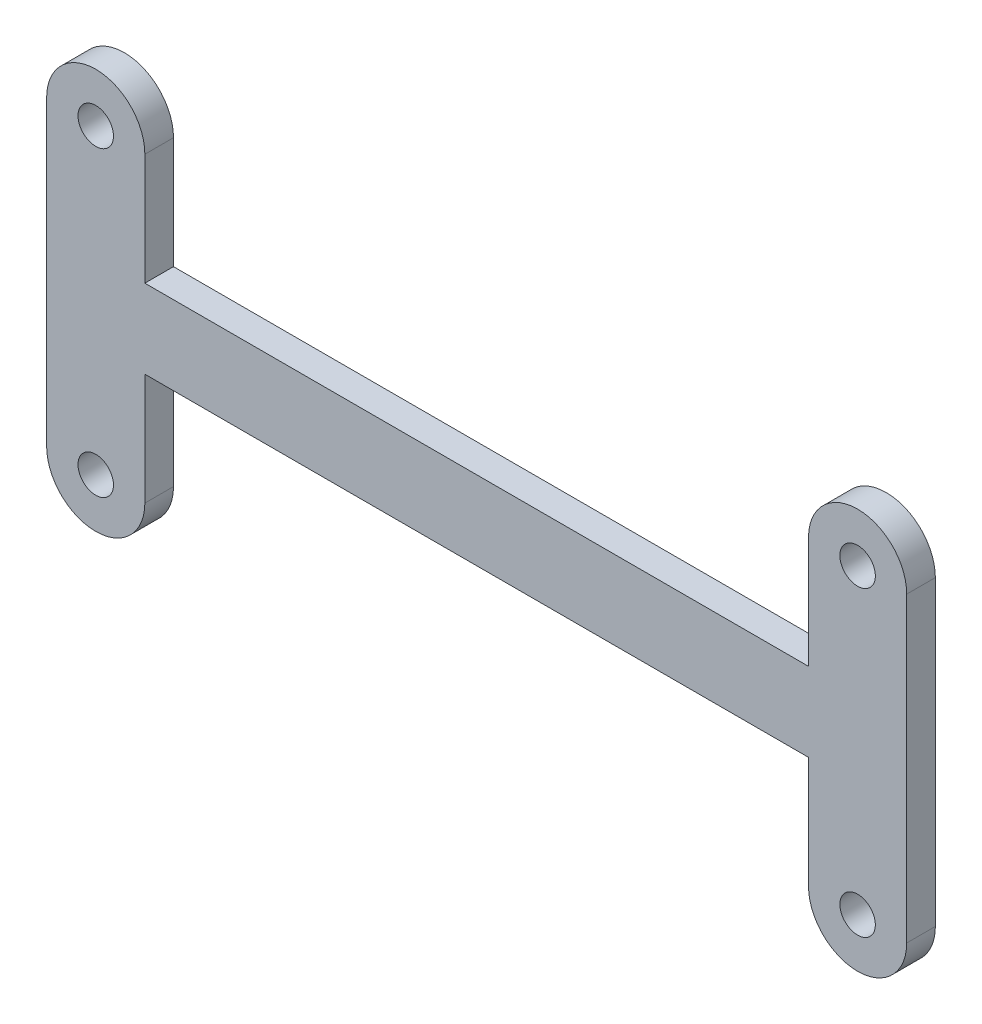
SolidWorks part; units mm, degrees
ref_plane "Front Plane" through (0, 0, 0) normal (0, 0, 1) x (1, 0, 0)
ref_plane "Top Plane" through (0, 0, 0) normal (0, 1, 0) x (1, 0, 0)
ref_plane "Right Plane" through (0, 0, 0) normal (1, 0, 0) x (0, 0, -1)
sketch "Sketch1" plane through (0, 0, 0) normal (0, 0, 1) x (1, 0, 0)
  line L0 (-25.2622, 11.5) -> (-25.2622, -11.5)
  line L1 (-32.7378, 11.5) -> (-32.7378, -11.5)
  line L2 (32.7378, 11.5) -> (32.7378, -11.5)
  line L3 (25.2622, -11.5) -> (25.2622, 11.5)
  line L4 (-25.2622, 0) -> (25.2622, 0) construction
  line L5 (-25.2622, 3) -> (25.2622, 3)
  line L6 (-25.2622, -3) -> (25.2622, -3)
  line L7 (0, -3) -> (0, 0) construction
  line L8 (0, 0) -> (0, 3) construction
  arc A0 (-29, 12.85) -> (-29, 10.15) centre (-29, 11.5) ccw construction
  arc A1 (-29, 10.15) -> (-29, 12.85) centre (-29, 11.5) ccw construction
  arc A2 (-29, 12.85) -> (-29, 10.15) centre (-29, 11.5) ccw
  arc A3 (-29, 10.15) -> (-29, 12.85) centre (-29, 11.5) ccw
  arc A4 (-29, -12.85) -> (-29, -10.15) centre (-29, -11.5) ccw construction
  arc A5 (-29, -10.15) -> (-29, -12.85) centre (-29, -11.5) ccw construction
  arc A6 (-29, -12.85) -> (-29, -10.15) centre (-29, -11.5) ccw
  arc A7 (-29, -10.15) -> (-29, -12.85) centre (-29, -11.5) ccw
  circle A8 centre (-29, 11.5) radius 3.7378
  circle A9 centre (-29, -11.5) radius 3.7378
  arc A10 (29, 12.85) -> (29, 10.15) centre (29, 11.5) ccw construction
  arc A11 (29, 10.15) -> (29, 12.85) centre (29, 11.5) ccw construction
  arc A12 (29, 12.85) -> (29, 10.15) centre (29, 11.5) ccw
  arc A13 (29, 10.15) -> (29, 12.85) centre (29, 11.5) ccw
  arc A14 (29, -10.15) -> (29, -12.85) centre (29, -11.5) ccw construction
  arc A15 (29, -12.85) -> (29, -10.15) centre (29, -11.5) ccw construction
  arc A16 (29, -10.15) -> (29, -12.85) centre (29, -11.5) ccw
  arc A17 (29, -12.85) -> (29, -10.15) centre (29, -11.5) ccw
  circle A18 centre (29, 11.5) radius 3.7378
  circle A19 centre (29, -11.5) radius 3.7378
  point P35 (25.2622, 3.8697)
  point P36 (0, 0)
  dimension "D1" = 6
extrude "Boss-Extrude1" add sketch "Sketch1" along normal blind 2.18 contours A8 A3 A2 | A9 L0 A8 L1 | A9 A7 A6 | L0 L6 L3 L5 | A19 L2 A18 L3 | A18 A13 A12 | A19 A17 A16
